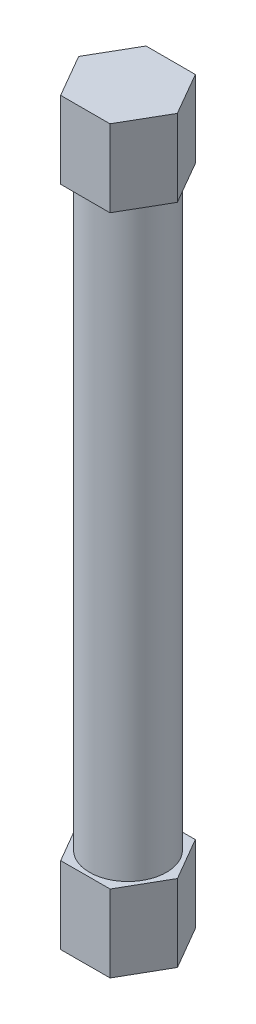
SolidWorks part; units mm, degrees
material "6061 Alloy"
ref_plane "Front Plane" through (0, 0, 0) normal (0, 0, 1) x (1, 0, 0)
ref_plane "Top Plane" through (0, 0, 0) normal (0, 1, 0) x (1, 0, 0)
ref_plane "Right Plane" through (0, 0, 0) normal (1, 0, 0) x (0, 0, -1)
sketch "Sketch1" plane through (0, 0, 0) normal (0, 1, 0) x (1, 0, 0)
  circle A0 centre (0, 0) radius 2.5
  dimension "D1" = 5
extrude "Boss-Extrude1" add sketch "Sketch1" along normal blind 38
sketch "Sketch2" plane through (0, 38, 0) normal (0, 1, 0) x (1, 0, 0)
  line L1 (3.2, 0) -> (1.6, 2.7713)
  line L2 (1.6, 2.7713) -> (-1.6, 2.7713)
  line L3 (-1.6, 2.7713) -> (-3.2, 0)
  line L4 (-3.2, 0) -> (-1.6, -2.7713)
  line L5 (-1.6, -2.7713) -> (1.6, -2.7713)
  line L6 (1.6, -2.7713) -> (3.2, 0)
  circle A0 centre (0, 0) radius 2.7713 construction
  dimension "D1" = 3.2
extrude "Boss-Extrude2" add sketch "Sketch2" along normal blind 5
sketch "Sketch3" plane through (0, 0, 0) normal (0, -1, 0) x (1, 0, 0)
  line L1 (3.2, -0.0097) -> (1.6084, 2.7664)
  line L2 (1.6084, 2.7664) -> (-1.5916, 2.7761)
  line L3 (-1.5916, 2.7761) -> (-3.2, 0.0097)
  line L4 (-3.2, 0.0097) -> (-1.6084, -2.7664)
  line L5 (-1.6084, -2.7664) -> (1.5916, -2.7761)
  line L6 (1.5916, -2.7761) -> (3.2, -0.0097)
  circle A0 centre (0, 0) radius 2.7713 construction
  dimension "D1" = 3.2
extrude "Boss-Extrude3" add sketch "Sketch3" along normal blind 5
